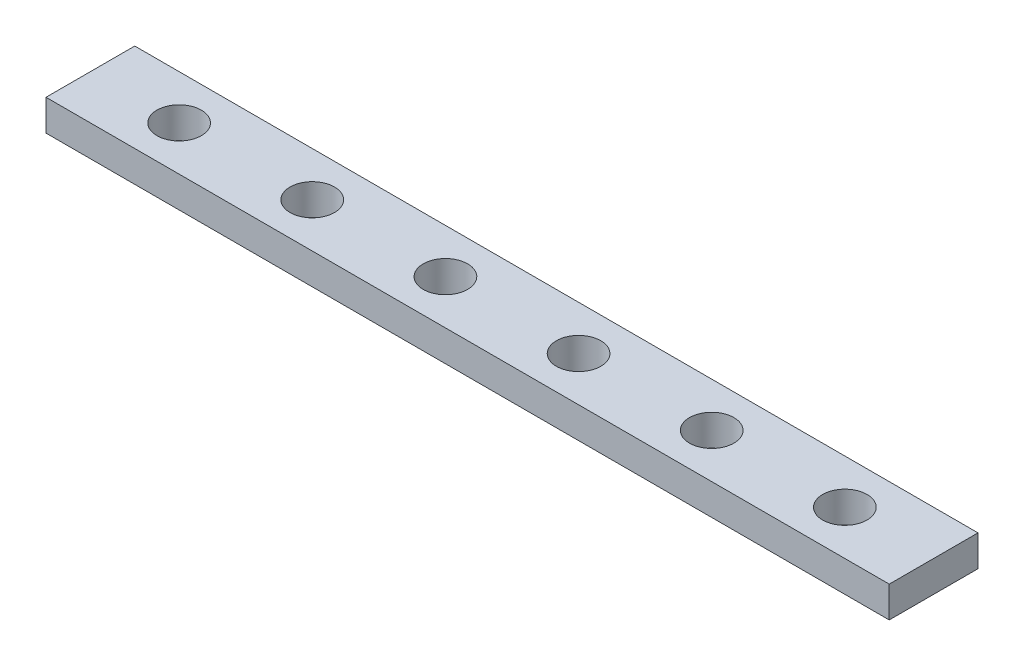
SolidWorks part; units mm, degrees
ref_plane "Front Plane" through (0, 0, 0) normal (0, 0, 1) x (1, 0, 0)
ref_plane "Top Plane" through (0, 0, 0) normal (0, 1, 0) x (1, 0, 0)
ref_plane "Right Plane" through (0, 0, 0) normal (1, 0, 0) x (0, 0, -1)
sketch "Sketch1" plane through (0, 0, 0) normal (0, 1, 0) x (1, 0, 0)
  line L1 (0, 0) -> (150, 0)
  line L2 (0, 0) -> (0, 10)
  line L3 (0, 10) -> (150, 10)
  line L4 (150, 0) -> (150, 10)
  circle A0 centre (145, 5) radius 2.5
  circle A1 centre (130, 5) radius 2.5
  circle A2 centre (115, 5) radius 2.5
  circle A3 centre (100, 5) radius 2.5
  circle A4 centre (85, 5) radius 2.5
  circle A5 centre (70, 5) radius 2.5
  circle A7 centre (55, 5) radius 2.5
  circle A8 centre (40, 5) radius 2.5
  circle A9 centre (25, 5) radius 2.5
  circle A10 centre (10, 5) radius 2.5
  point P9 (128.2922, 5.0386)
  point P10 (0, 0)
  point P12 (130.2789, 5.7944)
  point P14 (117.6278, 5)
  point P17 (105.5277, 5)
  point P20 (94.5465, 5)
  point P21 (94.7199, 5)
  point P24 (81.9731, 5)
  point P27 (66.3618, 5)
  point P30 (51.8963, 5)
  point P33 (35.7121, 5)
  point P36 (20.2862, 5)
  point P39 (6.8908, 5)
  dimension "D3" = 5
  dimension "D8" = 5
  dimension "D9" = 15
  dimension "D13" = 5
  dimension "D14" = 5
  dimension "D16" = 5
  dimension "D19" = 5
  dimension "D28" = 5
  dimension "D29" = 5
  dimension "D31" = 5
  dimension "D32" = 5
  dimension "D1" = 10
  dimension "D2" = 150
  dimension "D4" = 5
  dimension "D5" = 5
  dimension "D6" = 15
  dimension "D7" = 5
  dimension "D10" = 5
  dimension "D11" = 15
  dimension "D12" = 5
  dimension "D15" = 15
  dimension "D17" = 5
  dimension "D18" = 15
  dimension "D20" = 5
  dimension "D21" = 15
  dimension "D22" = 15
  dimension "D23" = 5
  dimension "D24" = 5
  dimension "D25" = 5
  dimension "D26" = 15
  dimension "D27" = 15
  dimension "D30" = 5
extrude "Boss-Extrude1" add sketch "Sketch1" along normal blind 6
sketch "Sketch2" plane through (150, 0, 0) normal (1, 0, 0) x (0, 0, -1)
  line L0 (0, 6) -> (0, 0)
  line L1 (0, 0) -> (10, 0)
  line L2 (10, 0) -> (10, 6)
  line L3 (10, 6) -> (0, 6)
extrude "Cut-Extrude1" cut sketch "Sketch2" against normal blind 55
sketch "Sketch3" plane through (0, 6, 0) normal (0, 1, 0) x (1, 0, 0)
  line L0 (0, 10) -> (95, 10)
  line L1 (95, 10) -> (95, 0)
  line L2 (95, 0) -> (0, 0)
  line L3 (0, 0) -> (0, 10)
extrude "Cut-Extrude2" cut sketch "Sketch3" against normal blind 2.5
